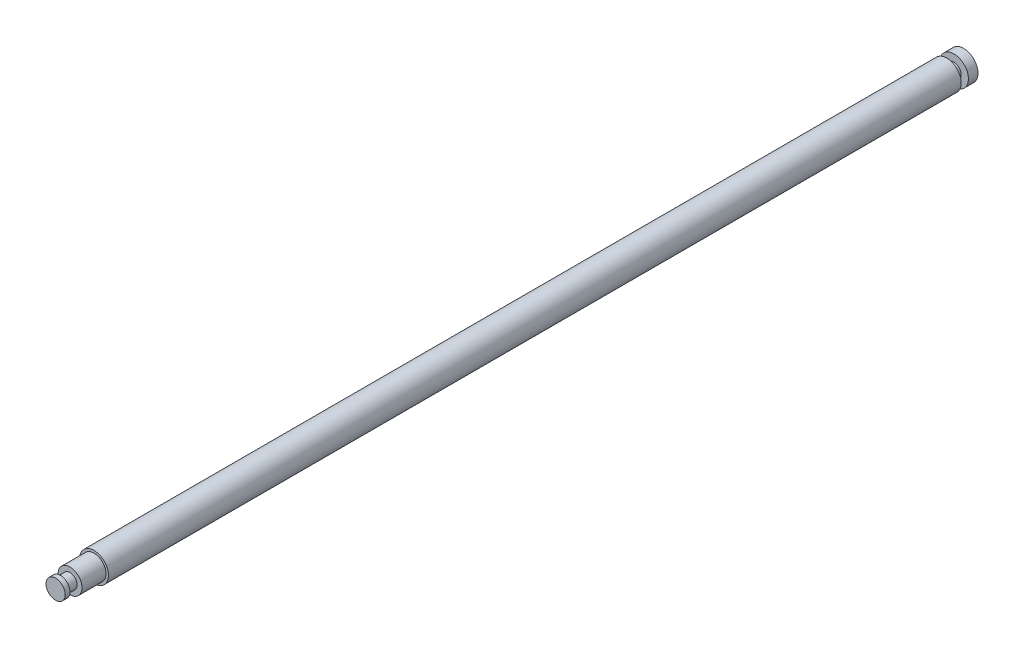
SolidWorks part; units mm, degrees
ref_plane "Alzado" through (0, 0, 0) normal (0, 0, 1) x (1, 0, 0)
ref_plane "Planta" through (0, 0, 0) normal (0, 1, 0) x (1, 0, 0)
ref_plane "Vista lateral" through (0, 0, 0) normal (1, 0, 0) x (0, 0, -1)
sketch "Croquis1" plane through (0, 0, 0) normal (1, 0, 0) x (0, 0, -1)
  line L0 (-94.5, 0) -> (94.5, 0) construction
  line L1 (-94.5, 0) -> (-94.5, 2)
  line L2 (-94.5, 2) -> (-93.5, 2)
  line L3 (-93.5, 2) -> (-93.5, 1.5)
  line L4 (-93.5, 1.5) -> (-91.5, 1.5)
  line L5 (-91.5, 1.5) -> (-91.5, 2.5)
  line L6 (-91.5, 2.5) -> (-86.5, 2.5)
  line L7 (-86.5, 2.5) -> (-86.5, 3)
  line L8 (-86.5, 3) -> (91, 3)
  line L9 (91, 3) -> (91, 1.5)
  line L10 (91, 1.5) -> (92.5, 1.5)
  line L11 (92.5, 1.5) -> (92.5, 3)
  line L12 (92.5, 3) -> (94.5, 3)
  line L13 (94.5, 3) -> (94.5, 0)
  line L14 (-94.5, 0) -> (94.5, 0)
  point P3 (0, 0)
  dimension "D1" = 8
  dimension "D2" = 4
  dimension "D3" = 3
  dimension "D4" = 5
  dimension "D5" = 1
  dimension "D6" = 189
  dimension "D7" = 3
  dimension "D8" = 6
  dimension "D9" = 6
  dimension "D10" = 1.5
  dimension "D11" = 2
  dimension "D12" = 5
revolve "Revolución1" add sketch "Croquis1" angle 360 about L0
